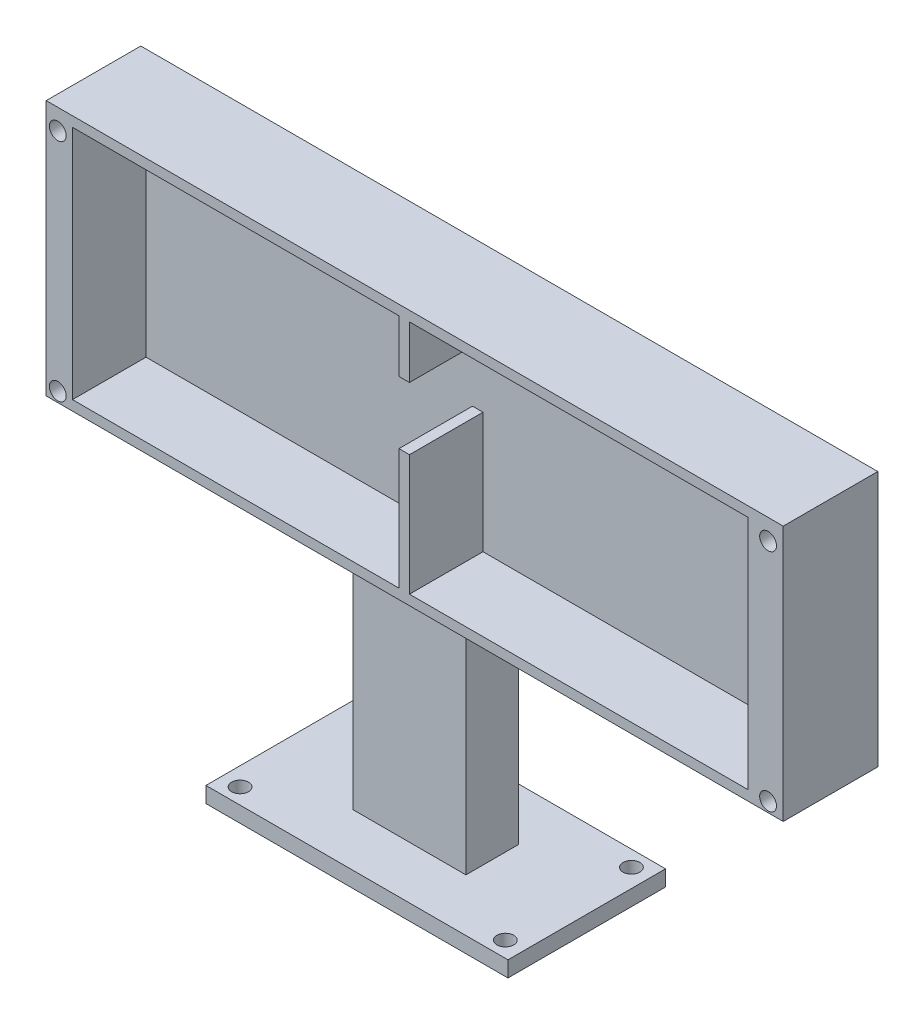
SolidWorks part; units mm, degrees
ref_plane "前视基准面" through (0, 0, 0) normal (0, 0, 1) x (1, 0, 0)
ref_plane "上视基准面" through (0, 0, 0) normal (0, 1, 0) x (1, 0, 0)
ref_plane "右视基准面" through (0, 0, 0) normal (1, 0, 0) x (0, 0, -1)
sketch "草图1" plane through (0, 0, 0) normal (0, 0, 1) x (1, 0, 0)
  line L0 (-39.5, 0) -> (18, 0)
  line L1 (18, 0) -> (18, 3)
  line L2 (18, 3) -> (0, 3)
  line L3 (0, 3) -> (0, 43)
  line L4 (0, 43) -> (54.4, 43)
  line L5 (54.4, 43) -> (54.4, 89.7)
  line L6 (54.4, 89.7) -> (-75.9, 89.7)
  line L7 (-75.9, 89.7) -> (-75.9, 43)
  line L8 (-75.9, 43) -> (-21.5, 43)
  line L9 (-21.5, 43) -> (-21.5, 3)
  line L10 (-21.5, 3) -> (-39.5, 3)
  line L11 (-39.5, 0) -> (-39.5, 3)
  line L12 (-11.75, 87.8) -> (-11.75, 44.9)
  line L17 (-10.75, 87.8) -> (-10.75, 44.9) construction
  line L18 (-73.9, 87.8) -> (52.4, 87.8)
  line L19 (-73.9, 87.8) -> (-73.9, 44.9)
  line L20 (-73.9, 44.9) -> (52.4, 44.9)
  line L21 (52.4, 87.8) -> (52.4, 44.9)
  line L26 (-9.75, 87.8) -> (-9.75, 44.9)
  line L27 (52.4, 79.8) -> (-73.9, 79.8) construction
  line L28 (-73.9, 67.9) -> (52.4, 67.9) construction
  line L29 (-21.5, 43) -> (0, 43) construction
  line L30 (-21.5, 3) -> (0, 3) construction
  dimension "D1" = 57.5
  dimension "D2" = 21.5
  dimension "D3" = 18
  dimension "D4" = 3
  dimension "D5" = 3
  dimension "D6" = 130.3
  dimension "D7" = 40
  dimension "D8" = 46.7
  dimension "D9" = 2
  dimension "D10" = 2
  dimension "D11" = 1.9
  dimension "D12" = 1.9
  dimension "D13" = 1
  dimension "D14" = 1
  dimension "D15" = 54.4
  dimension "D16" = 8
  dimension "D17" = 23
extrude "凸台-拉伸6" add sketch "草图1" along normal mid plane 30 contours L19 L20 L12 L18 | L18 L26 L20 L21 | L26 L18 L12 L20 | L11 L0 L1 L2 L3 L4 L5 L6 L7 L8 L9 L10 L18 L21 L20 L19
sketch "草图2" plane through (0, 0, 15) normal (0, 0, 1) x (1, 0, 0)
  line L0 (-75.9, 89.7) -> (-75.9, 43) construction
  line L1 (-73.9, 87.8) -> (52.4, 87.8)
  line L2 (-73.9, 87.8) -> (-73.9, 44.9)
  line L3 (-73.9, 44.9) -> (52.4, 44.9)
  line L4 (52.4, 87.8) -> (52.4, 44.9)
  line L5 (54.4, 89.7) -> (-75.9, 89.7) construction
  line L7 (-75.9, 43) -> (-21.5, 43) construction
  line L8 (54.4, 43) -> (54.4, 89.7) construction
  line L9 (-10.75, 87.8) -> (-10.75, 44.9) construction
  line L10 (-11.75, 87.8) -> (-11.75, 44.9)
  line L11 (-9.75, 87.8) -> (-9.75, 44.9)
  dimension "D1" = 2
  dimension "D2" = 1.9
  dimension "D3" = 1.9
  dimension "D4" = 2
  dimension "D5" = 1
  dimension "D6" = 1
extrude "切除-拉伸1" cut sketch "草图2" against normal blind 23 contours L10 L1 L2 L3 | L1 L11 L3 L4
sketch "草图4" plane through (-75.9, 0, 0) normal (-1, 0, 0) x (0, 0, 1)
  line L0 (-15, 43) -> (-15, 3) construction
  line L1 (-15, 3) -> (15, 3) construction
  line L2 (15, 3) -> (15, 43) construction
  line L3 (15, 43) -> (-15, 43) construction
  line L4 (15, 44.9) -> (15, 87.8) construction
  line L5 (15, 87.8) -> (-8, 87.8) construction
  line L6 (-8, 87.8) -> (-8, 44.9) construction
  line L7 (-8, 44.9) -> (15, 44.9) construction
  line L8 (-15, 43) -> (-15, 3)
  line L9 (-15, 3) -> (15, 3)
  line L10 (15, 3) -> (15, 43)
  line L11 (15, 43) -> (-15, 43)
  line L12 (15, 44.9) -> (15, 87.8)
  line L13 (15, 87.8) -> (-8, 87.8)
  line L14 (-8, 87.8) -> (-8, 44.9)
  line L15 (-8, 44.9) -> (15, 44.9)
  line L16 (5, 3) -> (5, 43)
  dimension "D1" = 10
extrude "切除-拉伸2" cut sketch "草图4" against normal through all contours L16 L9 L10 L11
sketch "草图5" plane through (-21.5, 0, 0) normal (-1, 0, 0) x (0, 0, 1)
  line L0 (-5, 3) -> (-5, 43)
  line L1 (15, 3) -> (-15, 3) construction
  line L2 (5, 43) -> (-15, 43) construction
  line L3 (-15, 43) -> (-15, 3) construction
  line M3 (5, 43) -> (-15, 43)
  line M4 (-15, 43) -> (-15, 3)
  line M5 (-15, 3) -> (5, 3)
  dimension "D1" = 10
extrude "切除-拉伸3" cut sketch "草图5" against normal through all and the other way through all contours L0 M5 M3 M4
sketch "草图6" plane through (-75.9, 0, 0) normal (-1, 0, 0) x (0, 0, 1)
  line L0 (15, 43) -> (-15, 43) construction
  line L1 (6, 43) -> (6, 89.7)
  line L2 (15, 89.7) -> (-15, 89.7) construction
  line L5 (15, 89.7) -> (15, 43) construction
  line M4 (-15, 43) -> (15, 43)
  line M5 (15, 43) -> (15, 89.7)
  line M6 (15, 89.7) -> (-15, 89.7)
  dimension "D2" = 9
extrude "切除-拉伸4" cut sketch "草图6" against normal through all and the other way through all contours L1 M4 M5 M6
sketch "草图7" plane through (-11.75, 0, 0) normal (-1, 0, 0) x (0, 0, 1)
  line L0 (-8, 79.8) -> (6, 79.8)
  line L1 (-8, 67.9) -> (6, 67.9)
  line L4 (-8, 44.9) -> (6, 44.9)
  line L5 (6, 44.9) -> (6, 87.8)
  line L6 (6, 87.8) -> (-8, 87.8)
  line L7 (-8, 87.8) -> (-8, 44.9)
  line L8 (-8, 44.9) -> (6, 44.9)
  line L9 (6, 44.9) -> (6, 87.8)
  line L10 (6, 87.8) -> (-8, 87.8)
  line L11 (-8, 87.8) -> (-8, 44.9)
  line M8 (6, 44.9) -> (6, 87.8)
  line M10 (-8, 87.8) -> (-8, 44.9)
  dimension "D2" = 8
  dimension "D3" = 23
  dimension "D1" = 0
extrude "切除-拉伸5" cut sketch "草图7" against normal blind 23 contours L1 L0 M10 M8
sketch "草图9" plane through (0, 0, 0) normal (0, -1, 0) x (1, 0, 0)
  line L0 (-39.5, 0) -> (18, 0) construction
  line L1 (-10.75, 15) -> (-10.75, -15) construction
  line L4 (-39.5, -15) -> (18, -15)
  line L5 (18, -15) -> (18, 15)
  line L6 (18, 15) -> (-39.5, 15)
  line L7 (-39.5, 15) -> (-39.5, -15)
  line L8 (-39.5, -15) -> (18, -15)
  line L9 (18, -15) -> (18, 15)
  line L10 (18, 15) -> (-39.5, 15)
  line L11 (-39.5, 15) -> (-39.5, -15)
  circle A0 centre (-36, 12) radius 1.6
  circle A1 centre (14.5, 12) radius 1.6
  circle A2 centre (-36, -12) radius 1.6
  circle A3 centre (14.5, -12) radius 1.6
  dimension "D2" = 3
  dimension "D3" = 3.5
  dimension "D4" = 3
  dimension "D5" = 3.5
  dimension "D6" = 3.5
  dimension "D7" = 3.5
  dimension "D8" = 3
  dimension "D9" = 3
  dimension "D1" = 0
extrude "切除-拉伸6" cut sketch "草图9" against normal blind 10 contours A0 | A2 | A1 | A3
sketch "草图10" plane through (-11.75, 0, 0) normal (-1, 0, 0) x (0, 0, 1)
  line L4 (6, 43) -> (6, 89.7)
  line L5 (6, 89.7) -> (-15, 89.7)
  line L6 (-15, 89.7) -> (-15, 43)
  line L7 (-15, 43) -> (6, 43)
  line L8 (6, 43) -> (6, 89.7)
  line L9 (6, 89.7) -> (-15, 89.7)
  line L10 (-15, 89.7) -> (-15, 43)
  line L11 (-15, 43) -> (6, 43)
  line L12 (6, 67.9) -> (-8, 67.9)
  line L13 (-8, 67.9) -> (-8, 44.9)
  line L14 (-8, 44.9) -> (6, 44.9)
  line L15 (6, 44.9) -> (6, 67.9)
  line L16 (6, 67.9) -> (-8, 67.9)
  line L17 (-8, 67.9) -> (-8, 44.9)
  line L18 (-8, 44.9) -> (6, 44.9)
  line L19 (6, 44.9) -> (6, 67.9)
  dimension "D1" = 0
  dimension "D2" = 0
sketch "草图11" plane through (-75.9, 0, 0) normal (-1, 0, 0) x (0, 0, 1)
  line L0 (-12, 89.7) -> (-12, 43)
  line L1 (6, 89.7) -> (-15, 89.7) construction
  line L2 (-15, 43) -> (6, 43) construction
  line L3 (-15, 89.7) -> (-15, 43) construction
  line M3 (6, 89.7) -> (-15, 89.7)
  line M4 (-15, 89.7) -> (-15, 43)
  line M5 (-15, 43) -> (6, 43)
  dimension "D1" = 3
extrude "切除-拉伸7" cut sketch "草图11" against normal through all and the other way through all contours L0 M3 M4 M5
sketch "草图14" plane through (0, 89.7, 0) normal (0, 1, 0) x (1, 0, 0)
  line L0 (54.4, 12) -> (61.4, 12)
  line L1 (61.4, 12) -> (61.4, -6)
  line L2 (61.4, -6) -> (54.4, -6)
  line L8 (54.4, 12) -> (-75.9, 12)
  line L9 (-75.9, 12) -> (-75.9, -6)
  line L10 (-75.9, -6) -> (54.4, -6)
  line L11 (54.4, -6) -> (54.4, 12)
  line L15 (54.4, -6) -> (54.4, 12)
  dimension "D1" = 0
  dimension "D2" = 7
extrude "凸台-拉伸8" add sketch "草图14" against normal blind 46.7
sketch "草图15" plane through (0, 0, 6) normal (0, 0, 1) x (1, 0, 0)
  line L0 (52.4, 87.8) -> (54.7156, 87.8)
  line L1 (54.7156, 87.8) -> (54.7156, 44.9)
  line L2 (54.7156, 44.9) -> (52.4, 44.9)
  line L3 (54.7156, 44.9) -> (58.5157, 44.9)
  line L4 (54.7156, 87.8) -> (58.5139, 87.8) construction
  line L12 (-11.75, 79.8) -> (-11.75, 87.8)
  line L13 (-11.75, 87.8) -> (-73.9, 87.8)
  line L14 (-73.9, 87.8) -> (-73.9, 44.9)
  line L15 (-73.9, 44.9) -> (-11.75, 44.9)
  line L16 (-11.75, 44.9) -> (-11.75, 67.9)
  line L17 (-11.75, 67.9) -> (-9.75, 67.9)
  line L18 (-9.75, 67.9) -> (-9.75, 44.9)
  line L19 (-9.75, 44.9) -> (52.4, 44.9)
  line L20 (52.4, 44.9) -> (52.4, 87.8)
  line L21 (52.4, 87.8) -> (-9.75, 87.8)
  line L22 (-9.75, 87.8) -> (-9.75, 79.8)
  line L23 (-9.75, 79.8) -> (-11.75, 79.8)
  line L24 (-11.75, 79.8) -> (-11.75, 87.8)
  line L25 (-11.75, 87.8) -> (-73.9, 87.8)
  line L26 (-73.9, 87.8) -> (-73.9, 44.9)
  line L27 (-73.9, 44.9) -> (-11.75, 44.9)
  line L28 (-11.75, 44.9) -> (-11.75, 67.9)
  line L29 (-11.75, 67.9) -> (-9.75, 67.9)
  line L30 (-9.75, 67.9) -> (-9.75, 44.9)
  line L31 (-9.75, 44.9) -> (52.4, 44.9)
  line L32 (52.4, 44.9) -> (52.4, 87.8)
  line L33 (52.4, 87.8) -> (-9.75, 87.8)
  line L34 (-9.75, 87.8) -> (-9.75, 79.8)
  line L35 (-9.75, 79.8) -> (-11.75, 79.8)
  circle A0 centre (58.5139, 87.8) radius 1.6
  circle A1 centre (58.5157, 44.9) radius 1.6
  dimension "D1" = 0
extrude "切除-拉伸9" cut sketch "草图15" against normal blind 14
sketch "草图19" plane through (0, 89.7, 0) normal (0, 1, 0) x (1, 0, 0)
  line L0 (-75.9, 12) -> (-78.9, 12)
  line L1 (-78.9, 12) -> (-78.9, -6)
  line L2 (-78.9, -6) -> (-75.9, -6)
  line L7 (61.4, 12) -> (-75.9, 12)
  line L8 (-75.9, 12) -> (-75.9, -6)
  line L9 (-75.9, -6) -> (61.4, -6)
  line L10 (61.4, -6) -> (61.4, 12)
  line L12 (-75.9, 12) -> (-75.9, -6)
  dimension "D1" = 3
  dimension "D2" = 0
extrude "凸台-拉伸9" add sketch "草图19" against normal blind 46.7
sketch "草图20" plane through (0, 0, 6) normal (0, 0, 1) x (1, 0, 0)
  line L0 (-78.9, 89.7) -> (-78.9, 91.7)
  line L1 (-78.9, 91.7) -> (61.4, 91.7)
  line L2 (61.4, 91.7) -> (61.4, 89.7)
  line L7 (61.4, 89.7) -> (-78.9, 89.7)
  line L8 (-78.9, 89.7) -> (-78.9, 43)
  line L9 (-78.9, 43) -> (61.4, 43)
  line L10 (61.4, 43) -> (61.4, 89.7)
  line L12 (-78.9, 89.7) -> (-78.9, 43)
  line L13 (-78.9, 43) -> (61.4, 43)
  line L14 (61.4, 43) -> (61.4, 89.7)
  line M10 (61.4, 89.7) -> (-78.9, 89.7)
  dimension "D1" = 2
  dimension "D2" = 0
extrude "凸台-拉伸10" add sketch "草图20" against normal blind 18 contours L2 L1 L0 M10
sketch "草图21" plane through (0, 0, 6) normal (0, 0, 1) x (1, 0, 0)
  line L0 (-76.7, 87.8) -> (-73.9, 87.8)
  line L1 (-76.7, 44.9) -> (-73.9, 44.9)
  line L2 (-73.9, 87.8) -> (-73.9, 89.8)
  line L3 (-73.9, 89.8) -> (54.7156, 89.8)
  line L4 (54.7156, 89.8) -> (54.7156, 87.8)
  line L5 (-11.75, 87.8) -> (-11.75, 89.7)
  line L6 (-11.75, 89.7) -> (-11.75, 43) construction
  line L7 (-11.75, 43) -> (-11.75, 89.7) construction
  line L8 (-9.75, 87.8) -> (-9.75, 89.8)
  line L11 (-11.75, 87.8) -> (-9.75, 87.8)
  circle A0 centre (-76.7, 87.8) radius 1.6
  circle A1 centre (-76.7, 44.9) radius 1.6
extrude "切除-拉伸13" cut sketch "草图21" against normal blind 14
sketch "草图23" plane through (0, 0, -8) normal (0, 0, 1) x (1, 0, 0)
  line L0 (-11.75, 87.8) -> (-11.75, 89.8)
  line L1 (-11.75, 43) -> (-11.75, 89.7) construction
  line L2 (-11.75, 89.7) -> (-11.75, 43) construction
  line L3 (-9.75, 87.8) -> (-9.75, 89.8)
  line L4 (-11.75, 87.8) -> (-9.75, 87.8)
  line L5 (-11.75, 89.8) -> (-9.75, 89.8)
  line L8 (54.7156, 44.9) -> (54.7156, 89.8)
  line L9 (54.7156, 89.8) -> (-73.9, 89.8)
  line L10 (-73.9, 89.8) -> (-73.9, 44.9)
  line L11 (-73.9, 44.9) -> (-11.75, 44.9)
  line L12 (-11.75, 44.9) -> (-11.75, 67.9)
  line L13 (-11.75, 67.9) -> (-9.75, 67.9)
  line L14 (-9.75, 67.9) -> (-9.75, 44.9)
  line L15 (-9.75, 44.9) -> (54.7156, 44.9)
  line L16 (54.7156, 44.9) -> (54.7156, 89.8)
  line L17 (54.7156, 89.8) -> (-73.9, 89.8)
  line L18 (-73.9, 89.8) -> (-73.9, 44.9)
  line L19 (-73.9, 44.9) -> (-11.75, 44.9)
  line L20 (-11.75, 44.9) -> (-11.75, 67.9)
  line L21 (-11.75, 67.9) -> (-9.75, 67.9)
  line L22 (-9.75, 67.9) -> (-9.75, 44.9)
  line L23 (-9.75, 44.9) -> (54.7156, 44.9)
  line M10 (54.7156, 89.8) -> (-73.9, 89.8)
  line M18 (-11.75, 87.8) -> (-9.75, 87.8)
  dimension "D1" = 0
extrude "凸台-拉伸11" add sketch "草图23" along normal blind 14 contours L3 L0 M18 M10
sketch "草图24" plane through (0, 0, 6) normal (0, 0, 1) x (1, 0, 0)
  line L4 (61.4, 43) -> (61.4, 91.7)
  line L5 (61.4, 91.7) -> (-78.9, 91.7)
  line L6 (-78.9, 91.7) -> (-78.9, 43)
  line L7 (-78.9, 43) -> (61.4, 43)
  line L8 (61.4, 43) -> (61.4, 91.7)
  line L9 (61.4, 91.7) -> (-78.9, 91.7)
  line L10 (-78.9, 91.7) -> (-78.9, 43)
  line L11 (-78.9, 43) -> (61.4, 43)
  dimension "D1" = 0
